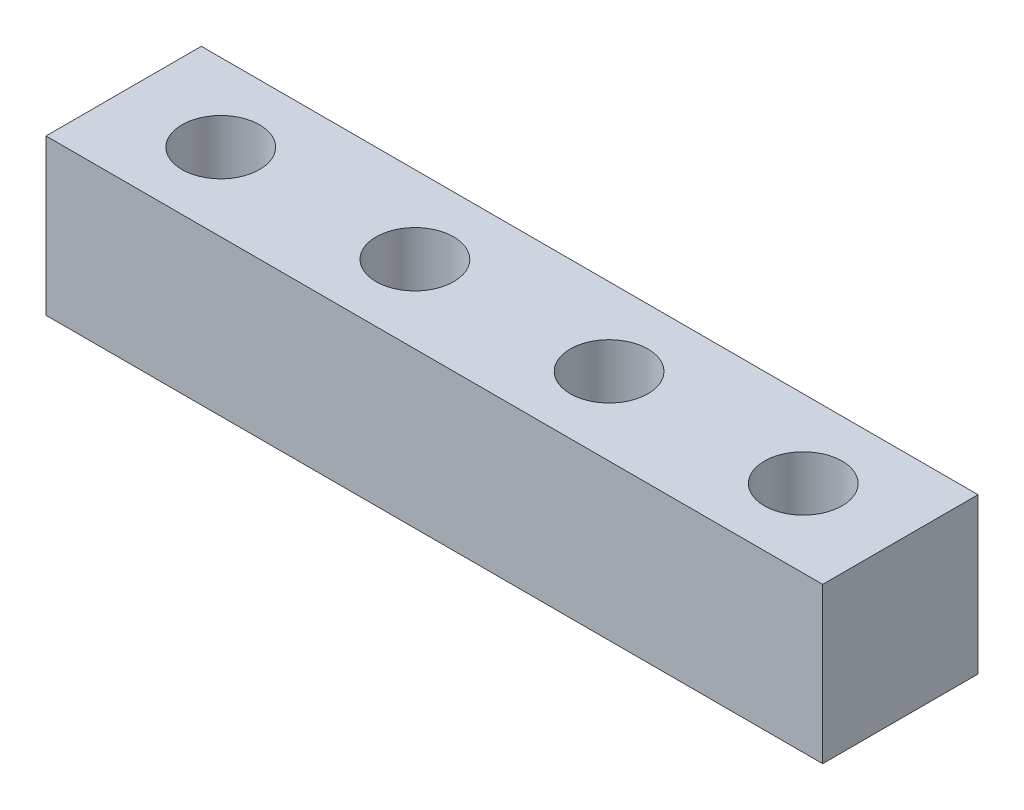
SolidWorks part; units mm, degrees
ref_plane "Front Plane" through (0, 0, 0) normal (0, 0, 1) x (1, 0, 0)
ref_plane "Top Plane" through (0, 0, 0) normal (0, 1, 0) x (1, 0, 0)
ref_plane "Right Plane" through (0, 0, 0) normal (1, 0, 0) x (0, 0, -1)
sketch "Sketch1" plane through (0, 0, 0) normal (0, 1, 0) x (1, 0, 0)
  line L0 (0, 1.5) -> (0, -1.5) construction
  line L1 (-7.5, -1.5) -> (7.5, -1.5)
  line L2 (-7.5, -1.5) -> (-7.5, 1.5)
  line L3 (-7.5, 1.5) -> (7.5, 1.5)
  line L4 (7.5, -1.5) -> (7.5, 1.5)
  line L5 (0, 1.5) -> (-7.5, 1.5) construction
  line L6 (-3.75, 1.5) -> (-3.75, -1.5) construction
  line L7 (-3.75, 0) -> (-7.5, 0) construction
  circle A0 centre (-5.625, 0) radius 0.75
  circle A1 centre (-1.875, 0) radius 0.75
  circle A2 centre (1.875, 0) radius 0.75
  circle A3 centre (5.625, 0) radius 0.75
  point P0 (0, 0)
  point P8 (0, 0)
  dimension "D3" = 4
  dimension "D1" = 3
  dimension "D2" = 15
extrude "Boss-Extrude1" add sketch "Sketch1" along normal blind 3
